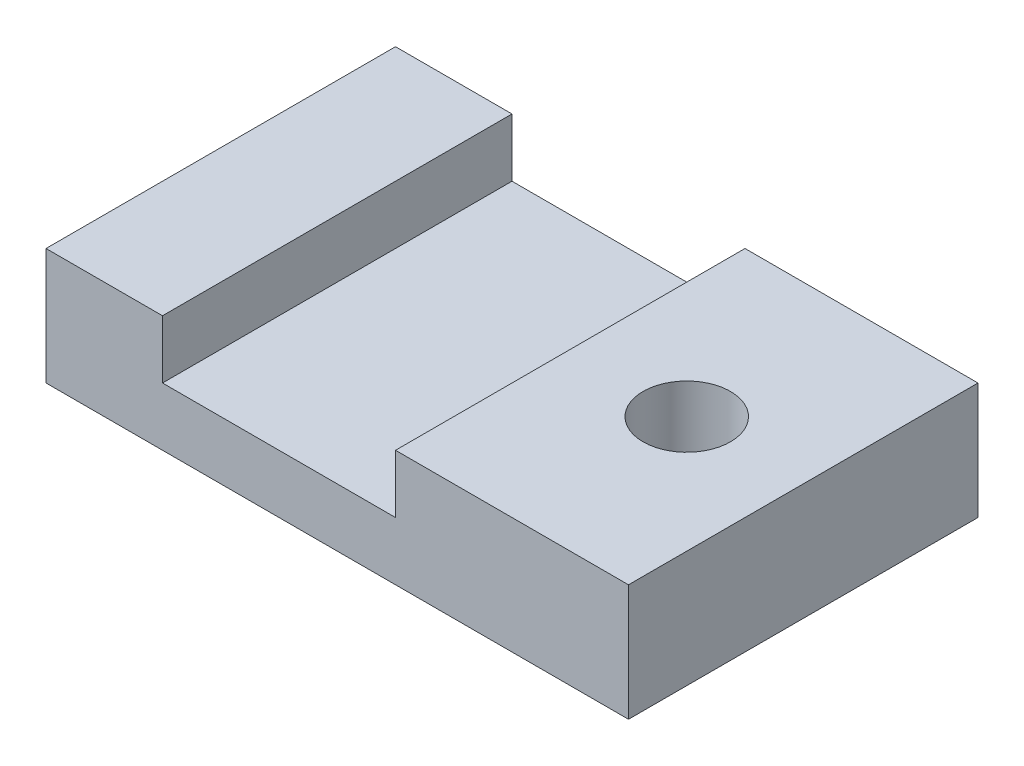
SolidWorks part; units mm, degrees
ref_plane "Front Plane" through (0, 0, 0) normal (0, 0, 1) x (1, 0, 0)
ref_plane "Top Plane" through (0, 0, 0) normal (0, 1, 0) x (1, 0, 0)
ref_plane "Right Plane" through (0, 0, 0) normal (1, 0, 0) x (0, 0, -1)
sketch "Sketch2" plane through (0, 0, 0) normal (0, 0, 1) x (1, 0, 0)
  line L0 (25.4, 25.4) -> (25.4, 12.7)
  line L1 (0, 0) -> (127, 0)
  line L2 (0, 0) -> (0, 25.4)
  line L3 (0, 25.4) -> (25.4, 25.4)
  line L4 (127, 0) -> (127, 25.4)
  line L5 (25.4, 12.7) -> (76.2, 12.7)
  line L6 (76.2, 12.7) -> (76.2, 25.4)
  line L7 (76.2, 25.4) -> (127, 25.4)
  dimension "D1" = 50.8
  dimension "D2" = 101.6
  dimension "D3" = 127
  dimension "D4" = 25.4
  dimension "D5" = 12.7
extrude "Boss-Extrude1" add sketch "Sketch2" against normal blind 76.2
sketch "Sketch3" plane through (0, 25.4, 0) normal (0, 1, 0) x (1, 0, 0)
  line L1 (127, 0) -> (76.2, 0) construction
  line L2 (127, 76.2) -> (127, 0) construction
  circle A0 centre (101.6, 38.1) radius 9.525
  dimension "D2" = 19.05
  dimension "D1" = 38.1
  dimension "D3" = 25.4
extrude "Cut-Extrude1" cut sketch "Sketch3" against normal through all
